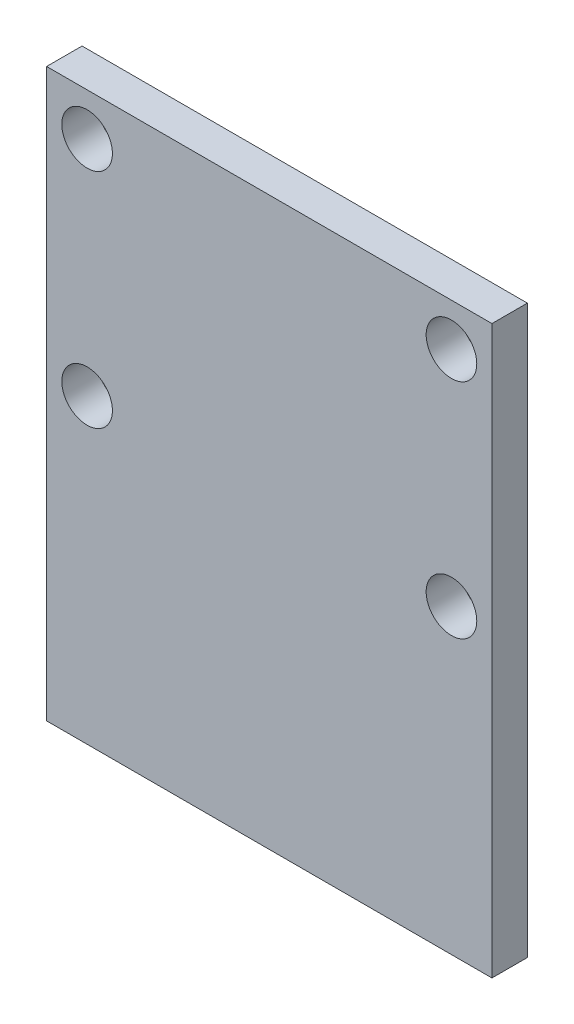
SolidWorks part; units mm, degrees
ref_plane "Front" through (0, 0, 0) normal (0, 0, 1) x (1, 0, 0)
ref_plane "Top" through (0, 0, 0) normal (0, 1, 0) x (1, 0, 0)
ref_plane "Right" through (0, 0, 0) normal (1, 0, 0) x (0, 0, -1)
sketch "Sketch1" plane through (0, 0, 0) normal (0, 0, 1) x (1, 0, 0)
  line L0 (11, 28) -> (11, 0) construction
  line L1 (0, 0) -> (22, 0)
  line L2 (0, 0) -> (0, 28)
  line L3 (0, 28) -> (22, 28)
  line L4 (22, 0) -> (22, 28)
  line L6 (20, 14.9) -> (2, 14.9)
  line L7 (20, 14.9) -> (20, 25.9)
  line L8 (20, 25.9) -> (2, 25.9)
  line L9 (2, 14.9) -> (2, 25.9)
  line L10 (20, 14.9) -> (2, 25.9) construction
  line L11 (20, 25.9) -> (2, 14.9) construction
  circle A0 centre (2, 25.9) radius 1.25
  circle A1 centre (2, 14.9) radius 1.25
  circle A2 centre (20, 14.9) radius 1.25
  circle A3 centre (20, 25.9) radius 1.25
  point P7 (11, 20.4)
  dimension "D6" = 2.5
  dimension "D1" = 22
  dimension "D2" = 28
  dimension "D3" = 18
  dimension "D4" = 11
  dimension "D5" = 2.1
extrude "Boss-Extrude1" add sketch "Sketch1" along normal blind 1.75 contours A3 L8 A0 L9 A1 L6 A2 L7 | L1 L4 L3 L2 A3 L7 A2 L6 A1 L9 A0 L8
sketch "Sketch2" plane through (0, 0, 0) normal (0, 0, -1) x (-1, 0, 0)
  line L0 (-20, 14.9) -> (-2, 25.9) construction
  circle A0 centre (-11, 20.4) radius 1
  dimension "D1" = 2
extrude "Boss-Extrude2" add sketch "Sketch2" along normal blind 1.25
